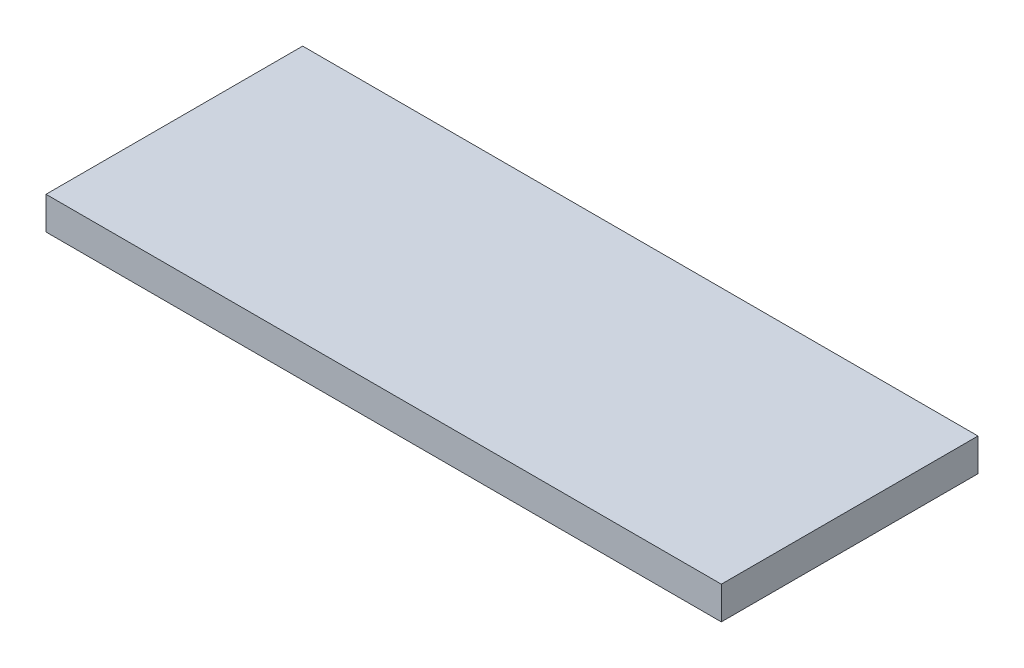
SolidWorks part; units mm, degrees
ref_plane "Front Plane" through (0, 0, 0) normal (0, 0, 1) x (1, 0, 0)
ref_plane "Top Plane" through (0, 0, 0) normal (0, 1, 0) x (1, 0, 0)
ref_plane "Right Plane" through (0, 0, 0) normal (1, 0, 0) x (0, 0, -1)
sketch "Sketch1" plane through (0, 0, 0) normal (0, 1, 0) x (1, 0, 0)
  line L1 (0, 0) -> (17.5768, 0)
  line L2 (0, 0) -> (0, 6.6802)
  line L3 (0, 6.6802) -> (17.5768, 6.6802)
  line L4 (17.5768, 0) -> (17.5768, 6.6802)
  dimension "D1" = 6.6802
  dimension "D2" = 17.5768
extrude "Boss-Extrude1" add sketch "Sketch1" along normal blind 0.8509
